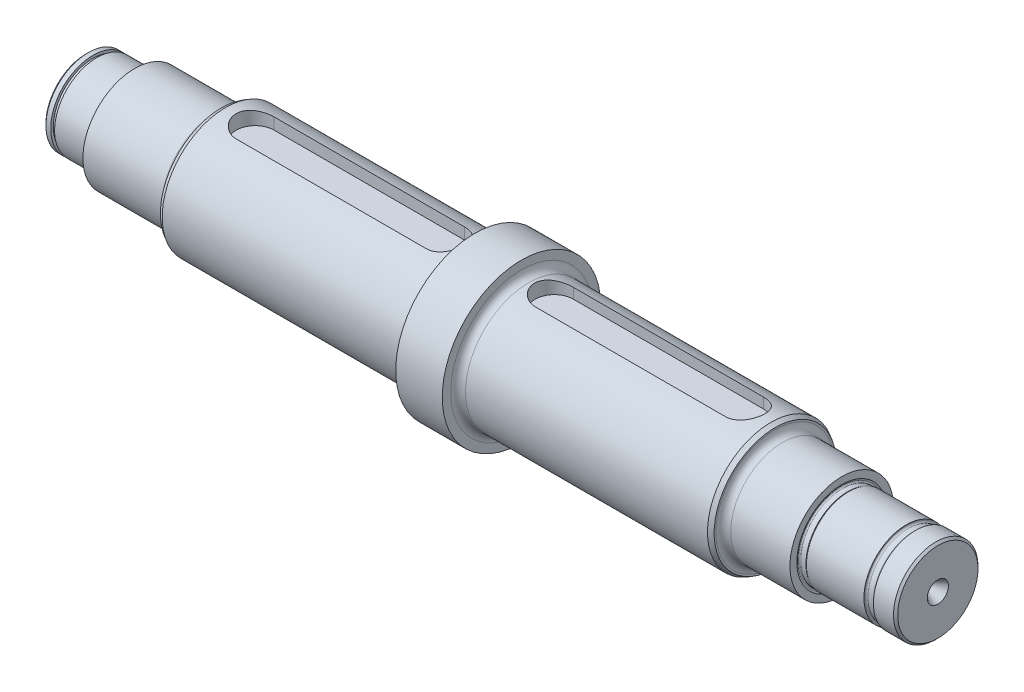
SolidWorks part; units mm, degrees
other "细节项目27"
other "细节项目28"
other "细节项目29"
other "细节项目30"
ref_plane "Front Plane" through (0, 0, 0) normal (0, 0, 1) x (1, 0, 0)
ref_plane "Top Plane" through (0, 0, 0) normal (0, 1, 0) x (1, 0, 0)
ref_plane "Right Plane" through (0, 0, 0) normal (1, 0, 0) x (0, 0, -1)
sketch "Sketch1" plane through (0, 0, 0) normal (0, 0, 1) x (1, 0, 0)
  line L0 (-10.2, 0) -> (-392.8, 0)
  line L1 (-403, 5) -> (-403, 19)
  line L2 (-402, 20) -> (-399.75, 20)
  line L3 (-380, 21.2) -> (-380, 24.5)
  line L4 (-380, 24.5) -> (-342.5, 24.5)
  line L5 (-339, 28) -> (-339, 28.8453)
  line L6 (-337, 30) -> (-222.5, 30)
  line L7 (-219, 33.5) -> (-219, 37.5)
  line L8 (0, 5) -> (0, 19)
  line L9 (-1, 20) -> (-10.51, 20)
  line L10 (-15, 20) -> (-15, 19.6)
  line L11 (-45.5, 24.5) -> (-73.5, 24.5)
  line L12 (-77, 28) -> (-77, 28.8453)
  line L13 (-79, 30) -> (-193.5, 30)
  line L14 (-197, 33.5) -> (-197, 37.5)
  line L15 (-197, 37.5) -> (-219, 37.5)
  line L16 (-403, 19) -> (-402, 20)
  line L17 (0, 19) -> (-1, 20)
  line L18 (-77, 28.8453) -> (-79, 30)
  line L19 (-339, 28.8453) -> (-337, 30)
  line L20 (-397.9, 20) -> (-382.4, 20)
  line L21 (-45.5, 23.2177) -> (-45.8, 23.2177)
  line L23 (-397.9, 20) -> (-397.9, 18.75)
  line L24 (-15, 20) -> (-42.2, 20)
  line L25 (-399.75, 20) -> (-399.75, 18.75)
  line L26 (-399.75, 18.75) -> (-397.9, 18.75)
  line L27 (-42.7196, 19.7) -> (-45.2, 19.7)
  line L28 (-9, 2) -> (-5, 2)
  line L29 (-45.5, 21.23) -> (-45.8, 20.4058)
  line L30 (-42.2, 20) -> (-42.7196, 19.7)
  line L31 (-392.8, 0) -> (-394, 2)
  line L32 (-10.51, 20) -> (-10.9719, 19.2)
  line L33 (-398, 2) -> (-403, 5)
  line L34 (-45.5, 21.23) -> (-45.5, 24.5)
  line L35 (-11.6647, 18.8) -> (-14.2, 18.8)
  line L37 (-394, 2) -> (-398, 2)
  line L38 (-5, 2) -> (0, 5)
  line L42 (-10.2, 0) -> (-9, 2)
  arc A0 (-342.5, 24.5) -> (-339, 28) centre (-342.5, 28) ccw
  arc A1 (-73.5, 24.5) -> (-77, 28) centre (-73.5, 28) cw
  arc A2 (-222.5, 30) -> (-219, 33.5) centre (-222.5, 33.5) ccw
  arc A3 (-193.5, 30) -> (-197, 33.5) centre (-193.5, 33.5) cw
  arc A4 (-11.6647, 18.8) -> (-10.9719, 19.2) centre (-11.6647, 19.6) ccw
  arc A5 (-382.4, 20) -> (-380, 21.2) centre (-381.5, 21.2) ccw
  arc A6 (-45.7638, 20.5052) -> (-45.2, 19.7) centre (-45.2, 20.3) ccw
  arc A7 (-15, 19.6) -> (-14.2, 18.8) centre (-14.2, 19.6) ccw
  point P4 (-403, 20)
  point P8 (-339, 30)
  point P11 (0, 20)
  point P15 (-77, 30)
  point P23 (-219, 30)
revolve "Revolve2" add sketch "Sketch1" angle 360 about L0
ref_plane "Plane1" through (0, 30, 0) normal (0, 1, 0) x (1, 0, 0)
sketch "Sketch2" plane through (0, 30, 0) normal (0, 1, 0) x (1, 0, 0)
  line L0 (-323, 0) -> (-233, 0) construction
  line L1 (-323, 9) -> (-233, 9)
  line L2 (-323, -9) -> (-233, -9)
  line L4 (-183, 1.5245) -> (-93, 1.5245) construction
  line L5 (-183, 10.5245) -> (-93, 10.5245)
  line L6 (-183, -7.4755) -> (-93, -7.4755)
  arc A0 (-323, 9) -> (-323, -9) centre (-323, 0) ccw
  arc A1 (-233, -9) -> (-233, 9) centre (-233, 0) ccw
  arc A2 (-183, 10.5245) -> (-183, -7.4755) centre (-183, 1.5245) ccw
  arc A3 (-93, -7.4755) -> (-93, 10.5245) centre (-93, 1.5245) ccw
  point P3 (-278, 0)
  point P10 (-138, 1.5245)
extrude "Cut-Extrude1" cut sketch "Sketch2" against normal blind 6.8
